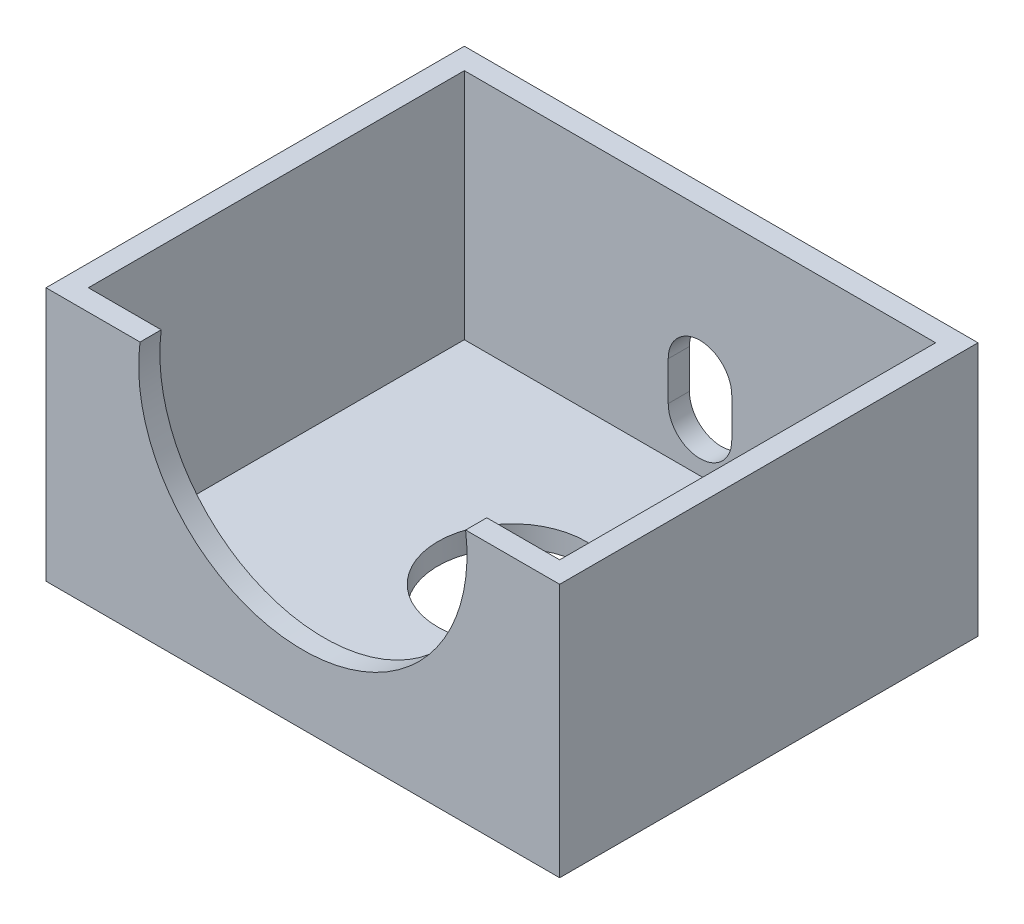
SolidWorks part; units mm, degrees
ref_plane "前视基准面" through (0, 0, 0) normal (0, 0, 1) x (1, 0, 0)
ref_plane "上视基准面" through (0, 0, 0) normal (0, 1, 0) x (1, 0, 0)
ref_plane "右视基准面" through (0, 0, 0) normal (1, 0, 0) x (0, 0, -1)
other "Configuration Table"
sketch "草图2" plane through (0, 0, 0) normal (0, 1, 0) x (1, 0, 0)
  line L1 (-24.25, 19.75) -> (24.25, 19.75)
  line L2 (-24.25, 19.75) -> (-24.25, -19.75)
  line L3 (-24.25, -19.75) -> (24.25, -19.75)
  line L4 (24.25, 19.75) -> (24.25, -19.75)
  line L5 (-24.25, 19.75) -> (24.25, -19.75) construction
  line L6 (-24.25, -19.75) -> (24.25, 19.75) construction
  point P0 (0, 0)
  dimension "D1" = 39.5
  dimension "D2" = 48.5
extrude "凸台-拉伸1" add sketch "草图2" along normal blind 2
sketch "草图4" plane through (0, 2, 0) normal (0, 1, 0) x (1, 0, 0)
  line L1 (-22.25, 17.75) -> (22.25, 17.75)
  line L2 (-22.25, 17.75) -> (-22.25, -17.75)
  line L3 (-22.25, -17.75) -> (22.25, -17.75)
  line L4 (22.25, 17.75) -> (22.25, -17.75)
  line L5 (-22.25, 17.75) -> (22.25, -17.75) construction
  line L6 (-22.25, -17.75) -> (22.25, 17.75) construction
  line L14 (24.25, -19.75) -> (24.25, 19.75)
  line L15 (24.25, 19.75) -> (-24.25, 19.75)
  line L16 (-24.25, 19.75) -> (-24.25, -19.75)
  line L17 (-24.25, -19.75) -> (24.25, -19.75)
  line L18 (24.25, -19.75) -> (24.25, 19.75)
  line L19 (24.25, 19.75) -> (-24.25, 19.75)
  line L20 (-24.25, 19.75) -> (-24.25, -19.75)
  line L21 (-24.25, -19.75) -> (24.25, -19.75)
  point P0 (0, 0)
  dimension "D1" = 44.5
  dimension "D2" = 35.5
  dimension "D3" = 0
extrude "凸台-拉伸2" add sketch "草图4" along normal blind 22
sketch "草图5" plane through (0, 0, 19.75) normal (0, 0, 1) x (1, 0, 0)
  line L0 (-24.25, 0) -> (24.25, 0) construction
  circle A0 centre (0, 22) radius 15.5
  dimension "D1" = 22
extrude "切除-拉伸1" cut sketch "草图5" against normal blind 10
sketch "草图6" plane through (0, 0, -19.75) normal (0, 0, -1) x (-1, 0, 0)
  line L0 (0, 0) -> (0, 18.093) construction
  line L1 (0, 10.0709) -> (0, 6.4036) construction
  line L2 (3, 10.0709) -> (3, 6.4036)
  line L3 (-3, 10.0709) -> (-3, 6.4036)
  arc A0 (3, 10.0709) -> (-3, 10.0709) centre (0, 10.0709) ccw
  arc A1 (-3, 6.4036) -> (3, 6.4036) centre (0, 6.4036) ccw
  point P5 (0, 8.2373)
  point P10 (0, 5.2576)
  point P11 (0, 6.4036)
  dimension "D1" = 6
extrude "切除-拉伸2" cut sketch "草图6" against normal blind 10
sketch "草图7" plane through (0, 0, 0) normal (0, -1, 0) x (1, 0, 0)
  circle A0 centre (0, 0) radius 7
extrude "切除-拉伸3" cut sketch "草图7" against normal blind 10
